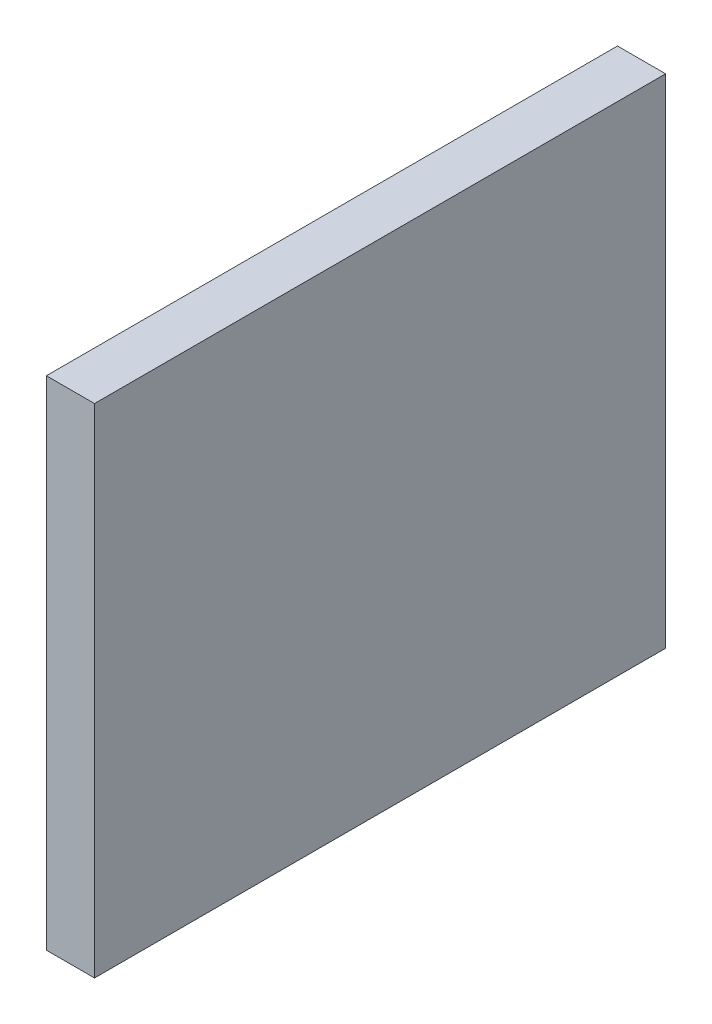
SolidWorks part; units mm, degrees
ref_plane "Front Plane" through (0, 0, 0) normal (0, 0, 1) x (1, 0, 0)
ref_plane "Top Plane" through (0, 0, 0) normal (0, 1, 0) x (1, 0, 0)
ref_plane "Right Plane" through (0, 0, 0) normal (1, 0, 0) x (0, 0, -1)
sketch "Sketch1" plane through (0, 0, 0) normal (0, 0, 1) x (1, 0, 0)
  line L0 (-210, -51.6228) -> (-210, -250) construction
  line L1 (-210, -53.1315) -> (-210, -250)
  line L2 (-210, -250) -> (-190.95, -250)
  line L3 (300, -250) -> (-300, -250) construction
  line L4 (-190.95, -250) -> (-190.95, -53.1315)
  line L5 (-202.3373, -53.1315) -> (202.3375, -53.1315) construction
  line L6 (-190.95, -53.1315) -> (-210, -53.1315)
extrude "Boss-Extrude1" add sketch "Sketch1" along normal up to surface (226 mm away)
